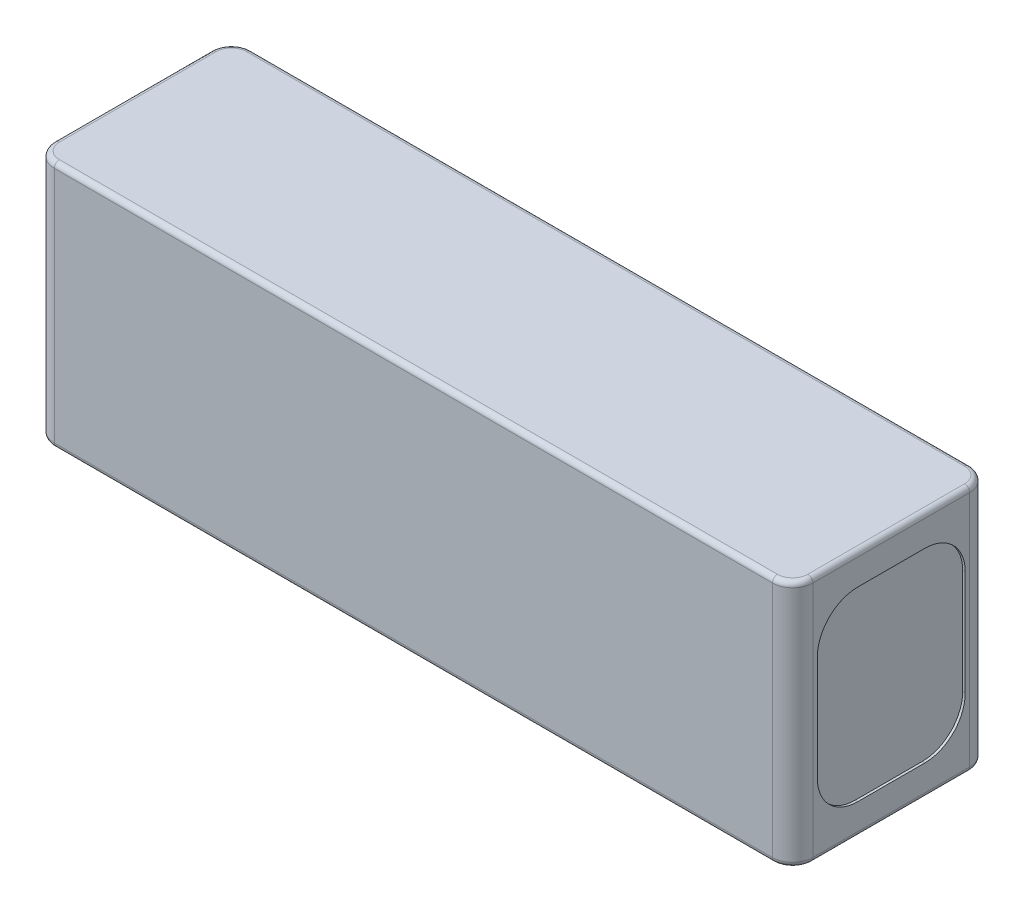
SolidWorks part; units mm, degrees
ref_plane "Front Plane" through (0, 0, 0) normal (0, 0, 1) x (1, 0, 0)
ref_plane "Top Plane" through (0, 0, 0) normal (0, 1, 0) x (1, 0, 0)
ref_plane "Right Plane" through (0, 0, 0) normal (1, 0, 0) x (0, 0, -1)
ref_plane "Plane1" through (0, 0, -15) normal (0, 0, -1) x (-1, 0, 0)
sketch "Sketch1" plane through (0, 0, -15) normal (0, 0, -1) x (-1, 0, 0)
  line L0 (-69, -22) -> (81, -22)
  line L1 (81, -22) -> (81, 27)
  line L2 (81, 27) -> (-69, 27)
  line L3 (-69, 27) -> (-69, -22)
  line L4 (-69, 2.5) -> (81, 2.5) construction
  line L5 (6, 27) -> (6, -22) construction
  dimension "D1" = 49
  dimension "D2" = 150
extrude "Boss-Extrude1" add sketch "Sketch1" against normal blind 39
sketch "Sketch2" plane through (69, 0, 0) normal (1, 0, 0) x (0, 0, -1)
  line L0 (-19.125, 12.875) -> (-19.125, -7.875)
  line L1 (-11.125, -15.875) -> (2.125, -15.875)
  line L2 (10.125, -7.875) -> (10.125, 12.875)
  line L3 (2.125, 20.875) -> (-11.125, 20.875)
  line L4 (-24, 27) -> (15, -22) construction
  line L5 (15, 27) -> (-24, -22) construction
  line L6 (-19.125, 20.875) -> (10.125, -15.875) construction
  line L7 (10.125, 20.875) -> (-19.125, -15.875) construction
  line L12 (-24, 27) -> (15, 27) construction
  line L13 (-24, 27) -> (-24, -22) construction
  line L14 (-24, -22) -> (15, -22) construction
  line L15 (15, 27) -> (15, -22) construction
  line L16 (-24, 27) -> (15, -22) construction
  line L17 (-24, -22) -> (15, 27) construction
  arc A0 (-19.125, -7.875) -> (-11.125, -15.875) centre (-11.125, -7.875) ccw
  arc A1 (2.125, -15.875) -> (10.125, -7.875) centre (2.125, -7.875) ccw
  arc A2 (10.125, 12.875) -> (2.125, 20.875) centre (2.125, 12.875) ccw
  arc A3 (-19.125, 12.875) -> (-11.125, 20.875) centre (-11.125, 12.875) cw
  point P16 (-4.5, 2.5)
  dimension "D3" = 8
  dimension "D1" = 29.25
  dimension "D2" = 39
extrude "Cut-Extrude1" cut sketch "Sketch2" against normal blind 0.5
sketch "Sketch3" plane through (-81, 0, 0) normal (-1, 0, 0) x (0, 0, 1)
  line L0 (11.125, 20.875) -> (-2.125, 20.875)
  line L1 (-10.125, 12.875) -> (-10.125, -7.875)
  line L2 (-2.125, -15.875) -> (11.125, -15.875)
  line L3 (19.125, -7.875) -> (19.125, 12.875)
  line L4 (-10.125, 20.875) -> (19.125, -15.875) construction
  line L5 (19.125, 20.875) -> (-10.125, -15.875) construction
  line L6 (-15, 27) -> (24, -22) construction
  line L7 (24, -22) -> (-15, -22) construction
  line L8 (-15, -22) -> (24, 27) construction
  arc A0 (-10.125, -7.875) -> (-2.125, -15.875) centre (-2.125, -7.875) ccw
  arc A1 (11.125, -15.875) -> (19.125, -7.875) centre (11.125, -7.875) ccw
  arc A2 (11.125, 20.875) -> (19.125, 12.875) centre (11.125, 12.875) cw
  arc A3 (-2.125, 20.875) -> (-10.125, 12.875) centre (-2.125, 12.875) ccw
  dimension "D3" = 8
  dimension "D1" = 29.25
  dimension "D2" = 39
extrude "Cut-Extrude2" cut sketch "Sketch3" against normal blind 0.5
fillet "Fillet1" radius 4 4 edges at (-81, 2.5, -15) (-81, 2.5, 24) (69, 2.5, -15) (69, 2.5, 24)
fillet "Fillet2" radius 1 16 edges at (67.8284, 27, -13.8284) (69, 27, 4.5) (-6, 27, -15) (67.8284, 27, 22.8284) (-79.8284, 27, -13.8284) (-6, 27, 24) (-81, 27, 4.5) (-79.8284, 27, 22.8284) (-81, -22, 4.5) (-79.8284, -22, -13.8284) (-79.8284, -22, 22.8284) (-6, -22, -15) (-6, -22, 24) (67.8284, -22, -13.8284) (67.8284, -22, 22.8284) (69, -22, 4.5)
sketch "Sketch4" plane through (0, 0, 24) normal (0, 0, 1) x (1, 0, 0)
  line L0 (-77, 2.5) -> (65, 2.5) construction
  line L1 (-77, 26) -> (-77, -21) construction
  line L2 (65, -21) -> (65, 26) construction
  line L3 (-6, 25.9735) -> (-6, -21) construction
  line L4 (-77, -21) -> (65, -21) construction
  circle A0 centre (-6, 2.5) radius 0.5026
equation "\"D1@Sketch3\"=\"D2@Sketch3\" * .75"
equation "\"D1@Sketch2\"=\"D2@Sketch2\"* .75"
